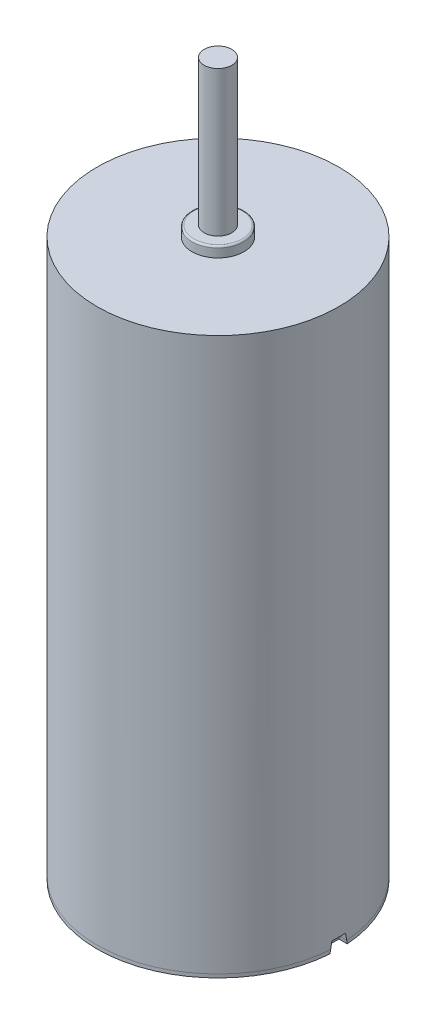
SolidWorks part; units mm, degrees
ref_plane "前视基准面" through (0, 0, 0) normal (0, 0, 1) x (1, 0, 0)
ref_plane "上视基准面" through (0, 0, 0) normal (0, 1, 0) x (1, 0, 0)
ref_plane "右视基准面" through (0, 0, 0) normal (1, 0, 0) x (0, 0, -1)
sketch "草图1" plane through (0, 0, 0) normal (0, 1, 0) x (1, 0, 0)
  circle A0 centre (0, 0) radius 3.5
  dimension "D1" = 7
extrude "凸台-拉伸1" add sketch "草图1" along normal blind 16
sketch "草图2" plane through (0, 0, 0) normal (0, -1, 0) x (1, 0, 0)
  line L0 (-4.1699, 0) -> (4.1861, 0) construction
sketch "草图3" plane through (0, 16, 0) normal (0, 1, 0) x (1, 0, 0)
  circle A0 centre (0, 0) radius 0.4
  dimension "D1" = 0.8
extrude "凸台-拉伸2" add sketch "草图3" along normal blind 4.5
sketch "草图4" plane through (0, 16, 0) normal (0, 1, 0) x (1, 0, 0)
  circle A0 centre (0, 0) radius 0.75
  dimension "D1" = 1.5
extrude "凸台-拉伸3" add sketch "草图4" along normal blind 0.3
fillet "圆角1" radius 0.05 1 edges at (0, 16.3, 0.75)
sketch "草图5" plane through (0, 0, 0) normal (0, -1, 0) x (1, 0, 0)
  circle A0 centre (0, 0) radius 3.5 construction
  circle A1 centre (0, 0) radius 3.5
extrude "凸台-拉伸4" add sketch "草图5" along normal blind 0.1 separate body
sketch "草图6" plane through (0, -0.1, 0) normal (0, -1, 0) x (1, 0, 0)
  line L0 (-4.1699, 0) -> (4.1861, 0) construction
  line L1 (3.75, 0.25) -> (3.25, 0.25)
  line L2 (3.75, 0.25) -> (3.75, -0.25)
  line L3 (3.75, -0.25) -> (3.25, -0.25)
  line L4 (3.25, 0.25) -> (3.25, -0.25)
  line L5 (3.75, 0.25) -> (3.25, -0.25) construction
  line L6 (3.75, -0.25) -> (3.25, 0.25) construction
  line L7 (0, 3.6338) -> (0, -3.1848) construction
  line L8 (-3.25, 0.25) -> (-3.25, -0.25)
  line L9 (-3.75, -0.25) -> (-3.25, -0.25)
  line L10 (-3.75, 0.25) -> (-3.75, -0.25)
  line L11 (-3.75, 0.25) -> (-3.25, 0.25)
  circle A0 centre (0, 0) radius 3.5 construction
  point P0 (3.5, 0)
  dimension "D1" = 0.5
  dimension "D2" = 0.5
extrude "切除-拉伸1" cut sketch "草图6" against normal blind 0.3 draft 10
equation "\"0。5\"=0.280478"
